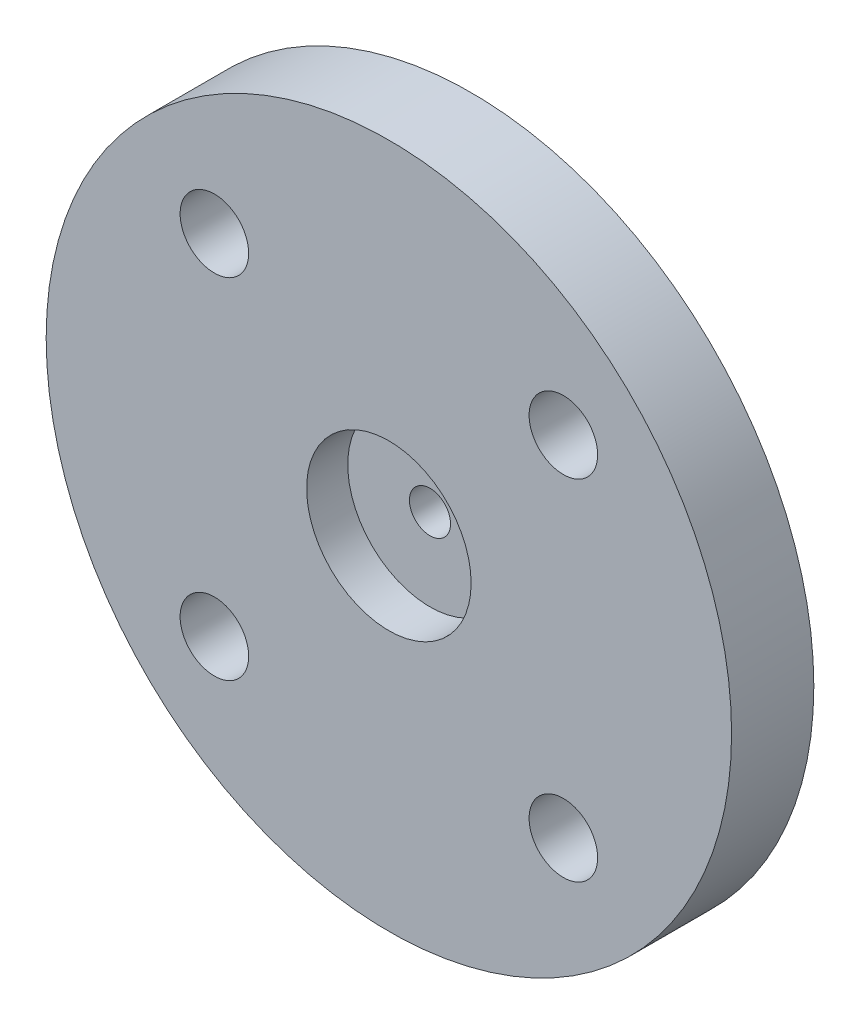
SolidWorks part; units mm, degrees
ref_plane "Front Plane" through (0, 0, 0) normal (0, 0, 1) x (1, 0, 0)
ref_plane "Top Plane" through (0, 0, 0) normal (0, 1, 0) x (1, 0, 0)
ref_plane "Right Plane" through (0, 0, 0) normal (1, 0, 0) x (0, 0, -1)
sketch "Sketch1" plane through (0, 0, 0) normal (0, 0, 1) x (1, 0, 0)
  line L0 (2.9074, -2.0654) -> (8.8308, -1.5412)
  line L1 (8.8308, 4.3673) -> (2.9074, 4.8915)
  line L2 (2.9074, 4.8915) -> (2.9074, 7.863)
  line L3 (-1.2926, 7.863) -> (-1.2926, 4.3984)
  line L4 (-1.4777, 4.2592) -> (-7.3613, 3.9377)
  line L5 (-7.3613, -1.1116) -> (-1.4777, -1.4331)
  line L6 (-1.2926, -1.5723) -> (-1.2926, -5.037)
  line L7 (2.9074, -5.037) -> (2.9074, -2.0654)
  circle A0 centre (0.8074, 1.413) radius 12.5
  arc A1 (8.8308, -1.5412) -> (9.3535, 1.153) centre (0.8074, 1.413) ccw
  arc A2 (9.3535, 1.6731) -> (9.3535, 1.153) centre (9.6574, 1.413) ccw
  arc A3 (9.3535, 1.6731) -> (8.8308, 4.3673) centre (0.8074, 1.413) ccw
  arc A4 (2.9074, 7.863) -> (-1.2926, 7.863) centre (0.8074, 7.863) ccw
  arc A5 (-1.2926, 4.3984) -> (-1.4777, 4.2592) centre (0.8074, 1.413) ccw
  arc A6 (-7.3613, 3.9377) -> (-7.7337, 1.8025) centre (0.8074, 1.413) ccw
  arc A7 (-7.7337, 1.0235) -> (-7.7337, 1.8025) centre (-7.6426, 1.413) ccw
  arc A8 (-7.7337, 1.0235) -> (-7.3613, -1.1116) centre (0.8074, 1.413) ccw
  arc A9 (-1.4777, -1.4331) -> (-1.2926, -1.5723) centre (0.8074, 1.413) ccw
  arc A10 (-1.2926, -5.037) -> (2.9074, -5.037) centre (0.8074, -5.037) ccw
  dimension "D1" = 25
extrude "Boss-Extrude1" add sketch "Sketch1" along normal blind 1.5
sketch "Sketch2" plane through (0, 0, 1.5) normal (0, 0, 1) x (1, 0, 0)
  circle A0 centre (0.8074, 1.413) radius 0.75
  circle A1 centre (0.8074, 1.413) radius 12.5
  circle A2 centre (0.8074, 1.413) radius 12.5
  dimension "D2" = 1.5
  dimension "D1" = 0
extrude "Boss-Extrude2" add sketch "Sketch2" along normal blind 3
sketch "Sketch3" plane through (0, 0, 4.5) normal (0, 0, 1) x (1, 0, 0)
  circle A0 centre (7.1714, 7.777) radius 1.25
  circle A1 centre (7.1714, -4.9509) radius 1.25
  circle A2 centre (-5.5565, -4.9509) radius 1.25
  circle A3 centre (-5.5565, 7.777) radius 1.25
  dimension "D2" = 2.5
  dimension "D3" = 4
extrude "Cut-Extrude1" cut sketch "Sketch3" against normal through all
sketch "Sketch4" plane through (0, 0, 0) normal (0, 0, -1) x (-1, 0, 0)
  circle A0 centre (-0.8074, 1.413) radius 9.5
  circle A1 centre (-0.8074, 1.413) radius 12.5
  dimension "D1" = 19
extrude "Cut-Extrude2" cut sketch "Sketch4" against normal blind 1.5
sketch "Sketch5" plane through (0, 0, 4.5) normal (0, 0, 1) x (1, 0, 0)
  circle A0 centre (0.8074, 1.413) radius 3
extrude "Cut-Extrude3" cut sketch "Sketch5" against normal blind 1.5
